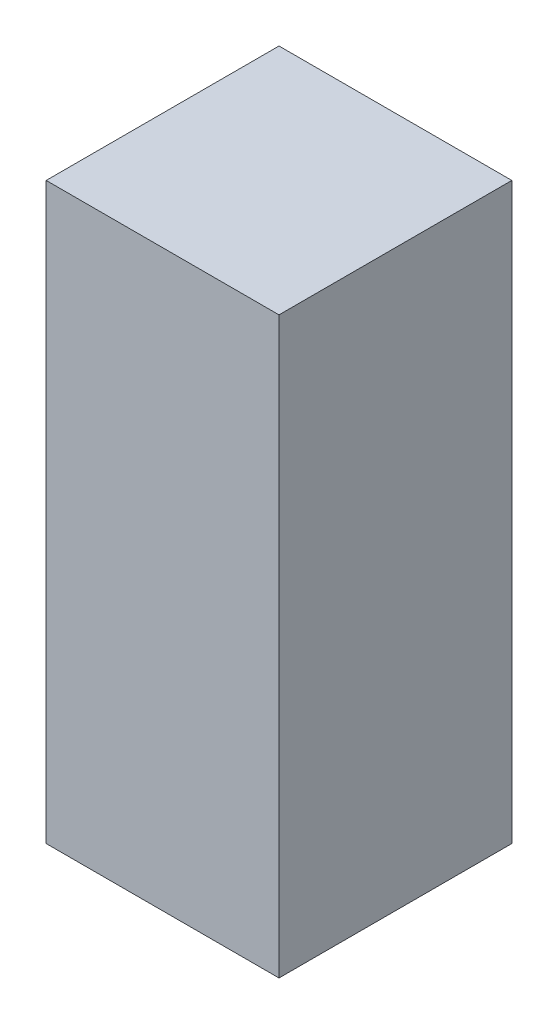
SolidWorks part; units mm, degrees
ref_plane "Front Plane" through (0, 0, 0) normal (0, 0, 1) x (1, 0, 0)
ref_plane "Top Plane" through (0, 0, 0) normal (0, 1, 0) x (1, 0, 0)
ref_plane "Right Plane" through (0, 0, 0) normal (1, 0, 0) x (0, 0, -1)
sketch "Sketch1" plane through (0, 0, 0) normal (0, 1, 0) x (1, 0, 0)
  line L1 (-18.6436, 18.6763) -> (19.4564, 18.6763)
  line L2 (-18.6436, 18.6763) -> (-18.6436, -19.4237)
  line L3 (-18.6436, -19.4237) -> (19.4564, -19.4237)
  line L4 (19.4564, 18.6763) -> (19.4564, -19.4237)
  dimension "D1" = 38.1
  dimension "D2" = 38.1
extrude "Boss-Extrude1" add sketch "Sketch1" along normal blind 93.98
